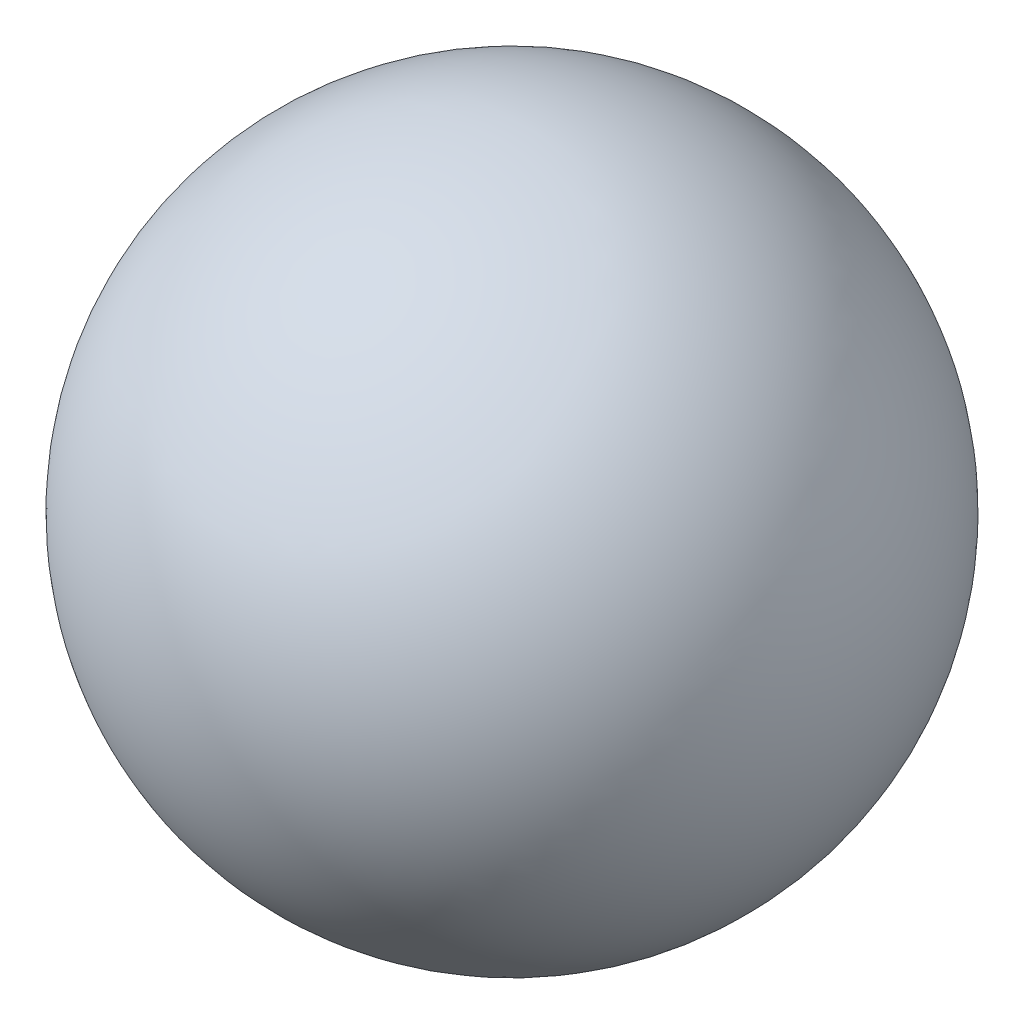
SolidWorks part; units mm, degrees
ref_plane "Front Plane" through (0, 0, 0) normal (0, 0, 1) x (1, 0, 0)
ref_plane "Top Plane" through (0, 0, 0) normal (0, 1, 0) x (1, 0, 0)
ref_plane "Right Plane" through (0, 0, 0) normal (1, 0, 0) x (0, 0, -1)
sketch "Sketch1" plane through (0, 0, 0) normal (0, 1, 0) x (1, 0, 0)
  line L0 (0, 110) -> (0, 105)
  line L1 (0, -105) -> (0, -110)
  arc A0 (0, -105) -> (0, 105) centre (0, 0) ccw
  arc A1 (0, -110) -> (0, 110) centre (0, 0) ccw
  dimension "D1" = 220
  dimension "D2" = 210
revolve "Revolve1" add sketch "Sketch1" angle 360 about L0
